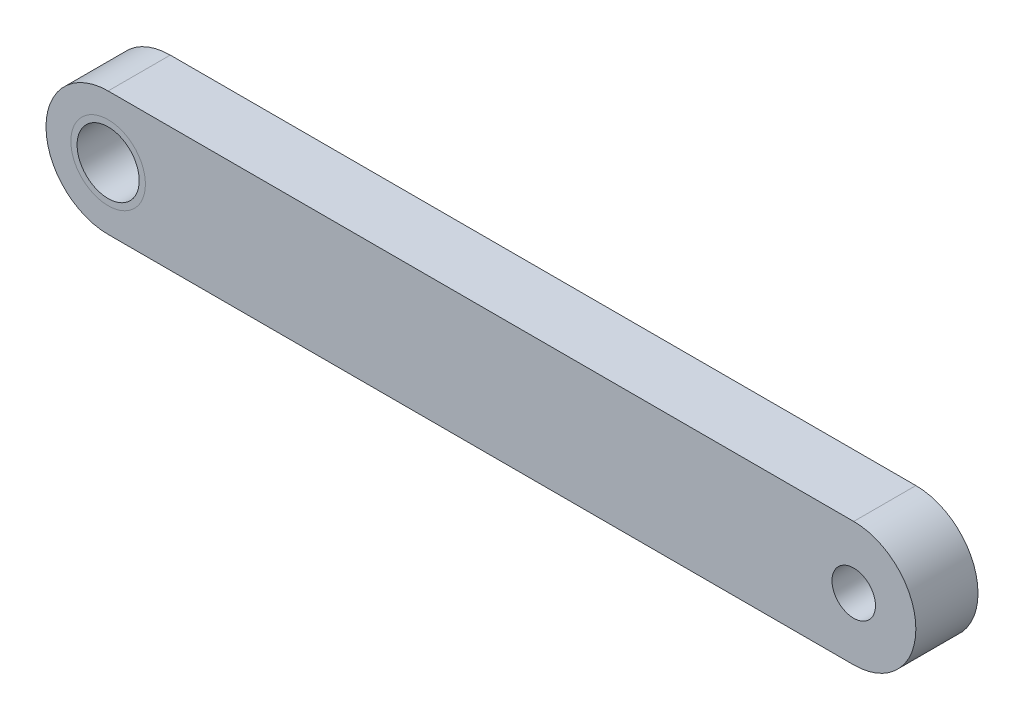
SolidWorks part; units mm, degrees
ref_plane "前视基准面" through (0, 0, 0) normal (0, 0, 1) x (1, 0, 0)
ref_plane "上视基准面" through (0, 0, 0) normal (0, 1, 0) x (1, 0, 0)
ref_plane "右视基准面" through (0, 0, 0) normal (1, 0, 0) x (0, 0, -1)
sketch "草图1" plane through (0, 0, 0) normal (0, 0, 1) x (1, 0, 0)
  line L0 (-69.9377, 26.0386) -> (-9.9377, 26.0386)
  line L1 (-69.9377, 16.0386) -> (-9.9377, 16.0386)
  arc A0 (-69.9377, 26.0386) -> (-69.9377, 16.0386) centre (-69.9377, 21.0386) ccw
  arc A1 (-9.9377, 26.0386) -> (-9.9377, 16.0386) centre (-9.9377, 21.0386) cw
  circle A2 centre (-69.9377, 21.0386) radius 3
  circle A3 centre (-9.9377, 21.0386) radius 3
  dimension "D1" = 5
extrude "凸台-拉伸1" add sketch "草图1" along normal mid plane 5
sketch "草图2" plane through (0, 0, 2.5) normal (0, 0, 1) x (1, 0, 0)
  circle A0 centre (-69.9377, 21.0386) radius 3
extrude "凸台-拉伸2" add sketch "草图2" against normal blind 5
sketch "草图3" plane through (0, 0, 2.5) normal (0, 0, 1) x (1, 0, 0)
  circle A0 centre (-69.9377, 21.0386) radius 1.75
extrude "切除-拉伸1" cut sketch "草图3" against normal blind 5
sketch "草图4" plane through (0, 0, 2.5) normal (0, 0, 1) x (1, 0, 0)
  circle A0 centre (-69.9377, 21.0386) radius 3
extrude "切除-拉伸2" cut sketch "草图4" against normal blind 10
sketch "草图5" plane through (0, 0, 2.5) normal (0, 0, 1) x (1, 0, 0)
  circle A0 centre (-9.9377, 21.0386) radius 3
extrude "凸台-拉伸4" add sketch "草图5" against normal blind 5
sketch "草图6" plane through (0, 0, 2.5) normal (0, 0, 1) x (1, 0, 0)
  circle A0 centre (-9.9377, 21.0386) radius 1.75
extrude "切除-拉伸3" cut sketch "草图6" against normal blind 5
sketch "草图7" plane through (0, 0, 2.5) normal (0, 0, 1) x (1, 0, 0)
  circle A0 centre (-69.9377, 21.0386) radius 3
extrude "凸台-拉伸5" add sketch "草图7" against normal blind 5 separate body
sketch "草图8" plane through (0, 0, 2.5) normal (0, 0, 1) x (1, 0, 0)
  circle A0 centre (-69.9377, 21.0386) radius 2.5
extrude "切除-拉伸4" cut sketch "草图8" against normal blind 5
